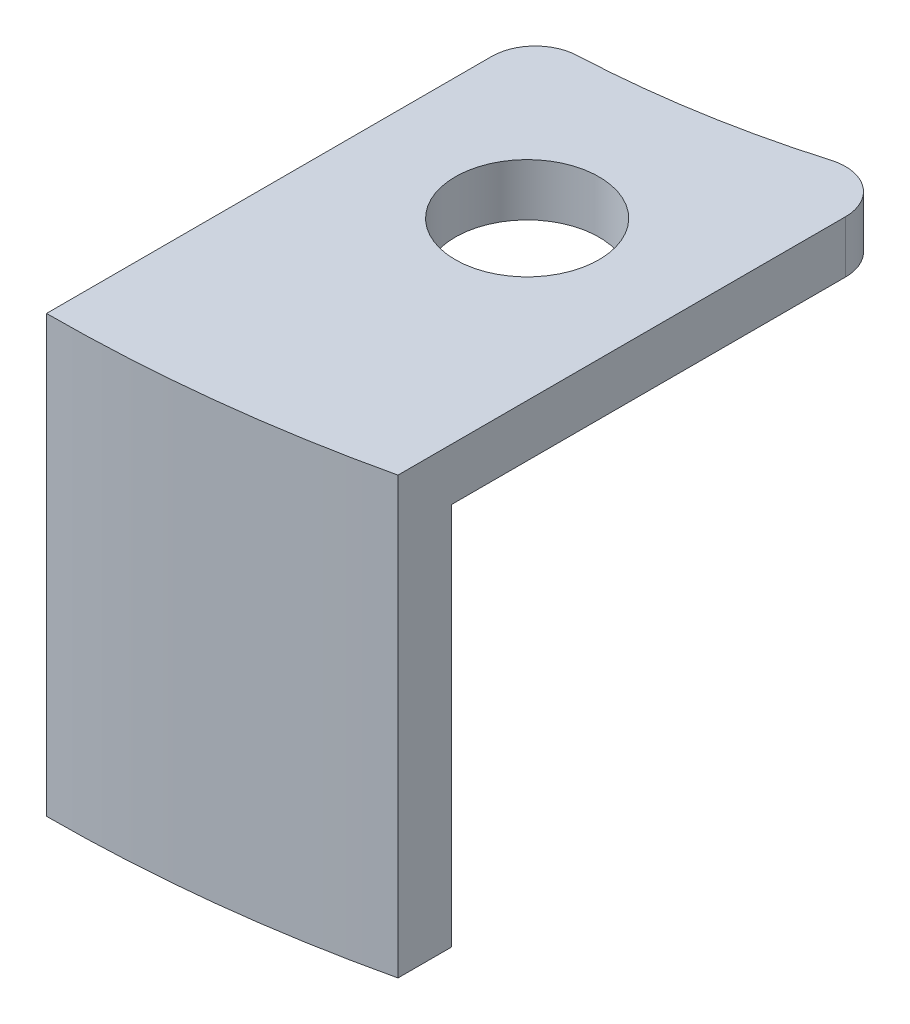
SolidWorks part; units mm, degrees
ref_plane "Front Plane" through (0, 0, 0) normal (0, 0, 1) x (1, 0, 0)
ref_plane "Top Plane" through (0, 0, 0) normal (0, 1, 0) x (1, 0, 0)
ref_plane "Right Plane" through (0, 0, 0) normal (1, 0, 0) x (0, 0, -1)
sketch "Sketch4" plane through (0, 0, 0) normal (0, 1, 0) x (1, 0, 0)
  line L0 (0, 0) -> (0, -20)
  line L1 (14.5, 2.55) -> (14.5, -18.2947)
  arc A0 (0, 0) -> (14.5, 2.55) centre (0, 42.5) ccw
  arc A1 (0, -20) -> (14.5, -18.2947) centre (0, 42.5) ccw
  point P5 (0, 0)
  point P6 (0, 0)
  dimension "D2" = 62.5
  dimension "D1" = 14.5
  dimension "D3" = 20
extrude "Boss-Extrude1" add sketch "Sketch4" against normal blind 2.4
sketch "Sketch6" plane through (0, 0, 0) normal (0, 1, 0) x (1, 0, 0)
  line L0 (0, -20) -> (0, -22.4)
  line L1 (14.5, -18.2947) -> (14.5, -20.7595)
  arc A0 (0, -20) -> (14.5, -18.2947) centre (0, 42.5) ccw construction
  arc A1 (0, -20) -> (14.5, -18.2947) centre (0, 42.5) ccw
  arc A2 (0, -22.4) -> (14.5, -20.7595) centre (0, 42.5) ccw
  arc A3 (0, -22.4) -> (15.0568, -20.6293) centre (0, 42.5) ccw construction
  dimension "D1" = 2.4
extrude "Boss-Extrude3" add sketch "Sketch6" against normal blind 20
fillet "Fillet2" radius 2 2 edges at (0, -1.2, 0) (14.5, -1.2, -2.55)
sketch "Sketch7" plane through (0, 0, 0) normal (0, 1, 0) x (1, 0, 0)
  line L0 (7.25, 0.6229) -> (7.25, -19.5781) construction
  line L1 (0, -1.955) -> (0, -22.4) construction
  line L2 (14.5, -20.7595) -> (14.5, -0.2083) construction
  line L3 (7.25, -19.5781) -> (7.25, -21.9938) construction
  arc A0 (0, -20) -> (14.5, -18.2947) centre (0, 42.5) ccw construction
  arc A2 (1.9101, 0.0429) -> (11.9382, 1.7112) centre (0, 42.5) ccw construction
  circle A3 centre (7.25, -7.5781) radius 3.3
  arc A4 (0, -20) -> (14.5, -18.2947) centre (0, 42.5) ccw construction
  arc A5 (0, -22.4) -> (14.5, -20.7595) centre (0, 42.5) ccw construction
  point P1 (0, 0)
  dimension "D2" = 6.6
  dimension "D1" = 12
extrude "Cut-Extrude1" cut sketch "Sketch7" against normal through all
